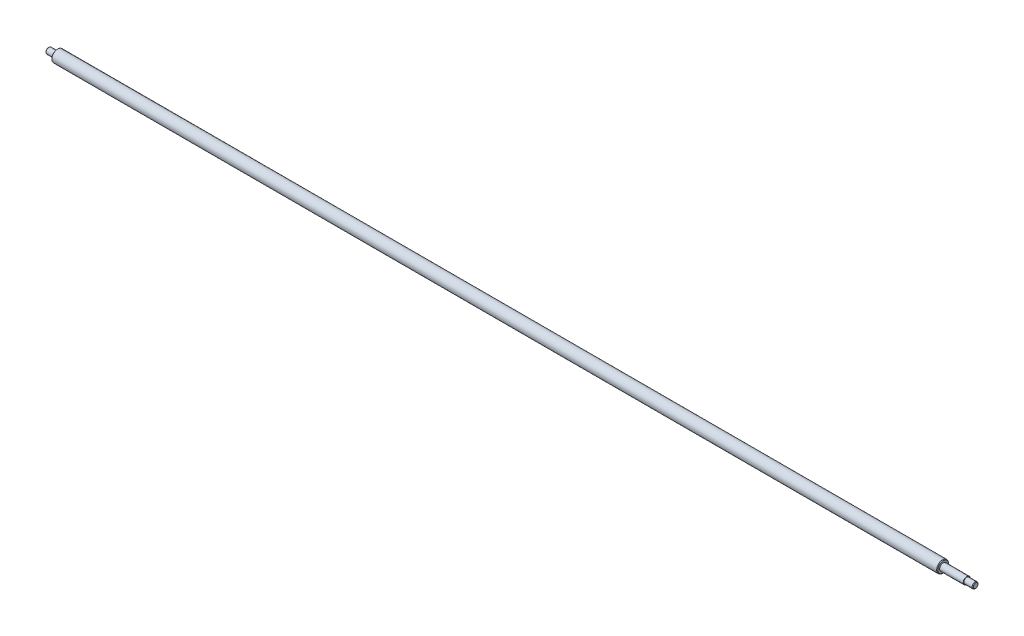
SolidWorks part; units mm, degrees
material "AISI Тип A2 Инструментальная сталь"
ref_plane "Спереди" through (0, 0, 0) normal (0, 0, 1) x (1, 0, 0)
ref_plane "Сверху" through (0, 0, 0) normal (0, 1, 0) x (1, 0, 0)
ref_plane "Справа" through (0, 0, 0) normal (1, 0, 0) x (0, 0, -1)
sketch "Эскиз1" plane through (0, 0, 0) normal (1, 0, 0) x (0, 0, -1)
  circle A0 centre (0, 0) radius 10
extrude "Бобышка-Вытянуть1" add sketch "Эскиз1" along normal blind 1500
sketch "Эскиз2" plane through (0, 0, 0) normal (-1, 0, 0) x (0, 0, 1)
  circle A0 centre (0, 0) radius 5
extrude "Бобышка-Вытянуть3" add sketch "Эскиз2" along normal blind 15
sketch "Эскиз3" plane through (1500, 0, 0) normal (1, 0, 0) x (0, 0, -1)
  circle A0 centre (0, 0) radius 6
extrude "Бобышка-Вытянуть4" add sketch "Эскиз3" along normal blind 40
sketch "Эскиз4" plane through (1540, 0, 0) normal (1, 0, 0) x (0, 0, -1)
  circle A0 centre (0, 0) radius 5
extrude "Бобышка-Вытянуть5" add sketch "Эскиз4" along normal blind 15
chamfer "Фаска4" distance 1 angle 45 2 edges at (1500, 0, -10) (1555, 0, -5)
chamfer "Фаска5" distance 1 angle 45 2 edges at (-15, 0, 5) (0, 0, -10)
